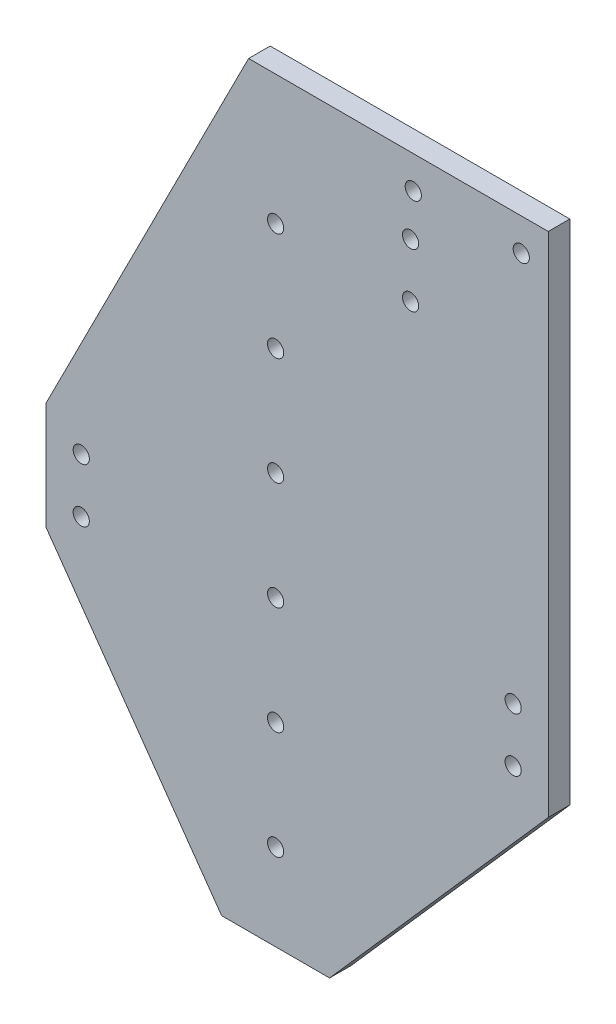
SolidWorks part; units mm, degrees
ref_plane "前视基准面" through (0, 0, 0) normal (0, 0, 1) x (1, 0, 0)
ref_plane "上视基准面" through (0, 0, 0) normal (0, 1, 0) x (1, 0, 0)
ref_plane "右视基准面" through (0, 0, 0) normal (1, 0, 0) x (0, 0, -1)
other "Configuration Table"
sketch "草图1" plane through (0, 0, 0) normal (0, 0, 1) x (1, 0, 0)
  line L0 (0, 0) -> (0, 94)
  line L4 (-46.5, -46) -> (-46.5, 94) construction
  line L5 (-93, 10) -> (-50.5, 10) construction
  line L6 (-86.5, 10) -> (-86.5, 0) construction
  line L7 (-93, 0) -> (-60.5, -46)
  line L8 (-60.5, -46) -> (-40.5, -46)
  line L9 (-40.5, -46) -> (0, 0)
  line L10 (-93, 0) -> (0, 0) construction
  line L11 (-25.5, 80) -> (-25.5, 70) construction
  line L12 (-50.5, 10) -> (-50.5, 30) construction
  line L13 (0, 88) -> (-5, 88) construction
  line L14 (-5, 88) -> (-25, 88) construction
  line L16 (-55.5, 94) -> (0, 94)
  line L18 (-93, 0) -> (-93, 20)
  line L19 (-93, 20) -> (-55.5, 94)
  line L20 (-25.5, 80) -> (-25.5, 94) construction
  line L21 (-50.5, -46) -> (-50.5, -30) construction
  line L22 (-50.5, 50) -> (-50.5, 94) construction
  circle A0 centre (-86.5, 15) radius 1.5
  circle A1 centre (-86.5, 5) radius 1.5
  circle A2 centre (-6.5, 5) radius 1.5
  circle A3 centre (-6.5, 15) radius 1.5
  circle A4 centre (-25.5, 80) radius 1.5
  circle A5 centre (-25.5, 70) radius 1.5
  circle A6 centre (-50.5, 10) radius 1.5
  circle A7 centre (-50.5, 30) radius 1.5
  circle A8 centre (-50.5, 50) radius 1.5
  circle A9 centre (-50.5, -10) radius 1.5
  circle A10 centre (-50.5, -30) radius 1.5
  circle A11 centre (-5, 88) radius 1.5
  circle A12 centre (-25, 88) radius 1.5
  circle A14 centre (-50.5, 70) radius 1.5
  point P4 (-46.5, 0)
  point P17 (-86.5, 5)
  point P48 (-93, 10)
  dimension "D1" = 3
  dimension "D3" = 4
  dimension "D4" = 80
  dimension "D10" = 3
  dimension "D12" = 93
  dimension "D13" = 3
  dimension "D17" = 20
  dimension "D21" = 3
  dimension "D2" = 20
  dimension "D5" = 94
  dimension "D6" = 10
  dimension "D7" = 46
  dimension "D9" = 10
  dimension "D11" = 5
  dimension "D15" = 20
  dimension "D18" = 5
  dimension "D19" = 6
  dimension "D20" = 20
  dimension "D22" = 21
  dimension "D23" = 8
  dimension "D8" = 2
  dimension "D14" = 4
  dimension "D16" = 3
extrude "凸台-拉伸1" add sketch "草图1" along normal blind 4
